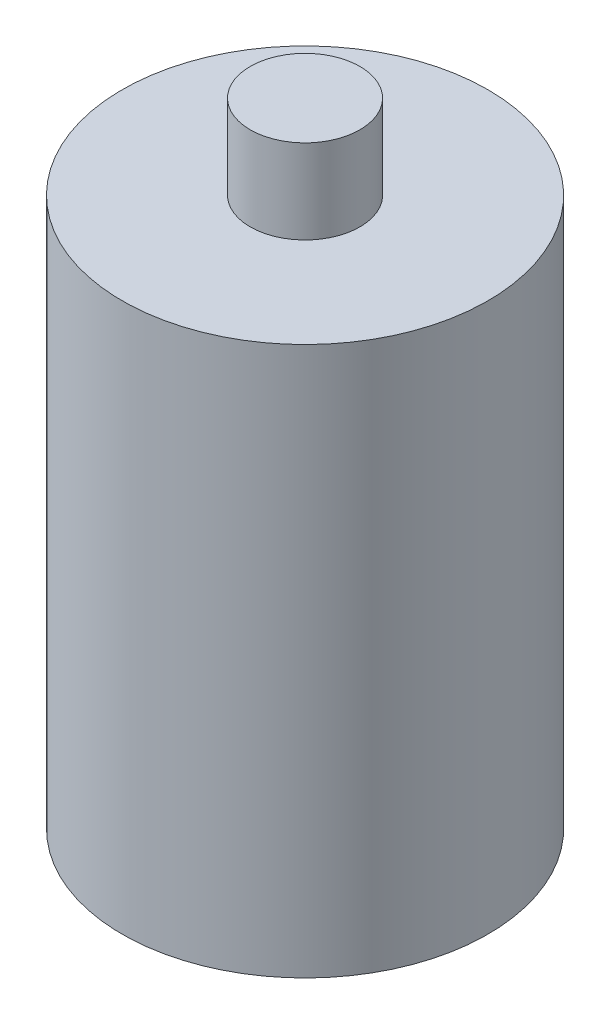
SolidWorks part; units mm, degrees
ref_plane "Front Plane" through (0, 0, 0) normal (0, 0, 1) x (1, 0, 0)
ref_plane "Top Plane" through (0, 0, 0) normal (0, 1, 0) x (1, 0, 0)
ref_plane "Right Plane" through (0, 0, 0) normal (1, 0, 0) x (0, 0, -1)
sketch "Sketch1" plane through (0, 0, 0) normal (0, 1, 0) x (1, 0, 0)
  circle A0 centre (0, 0) radius 12.7
  dimension "D1" = 25.4
extrude "Boss-Extrude1" add sketch "Sketch1" along normal blind 38.1
sketch "Sketch2" plane through (0, 38.1, 0) normal (0, 1, 0) x (1, 0, 0)
  circle A0 centre (0, 0) radius 3.81
  dimension "D1" = 7.62
extrude "Boss-Extrude2" add sketch "Sketch2" along normal blind 5.842
